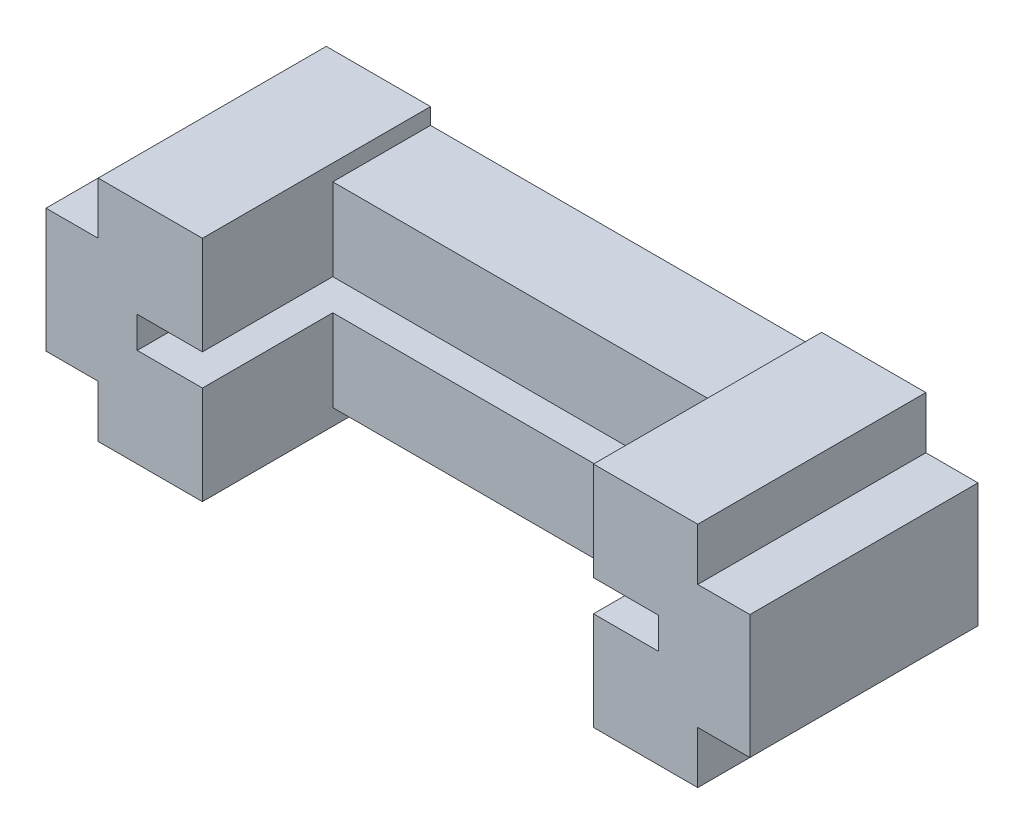
SolidWorks part; units mm, degrees
ref_plane "Front Plane" through (0, 0, 0) normal (0, 0, 1) x (1, 0, 0)
ref_plane "Top Plane" through (0, 0, 0) normal (0, 1, 0) x (1, 0, 0)
ref_plane "Right Plane" through (0, 0, 0) normal (1, 0, 0) x (0, 0, -1)
sketch "Sketch1" plane through (0, 0, 0) normal (0, 0, 1) x (1, 0, 0)
  line L1 (-29.21, -11.1125) -> (29.21, -11.1125)
  line L2 (-34.29, -6.0325) -> (-34.29, 6.0325)
  line L3 (-29.21, 11.1125) -> (29.21, 11.1125)
  line L4 (34.29, -6.0325) -> (34.29, 6.0325)
  line L9 (-34.29, 6.0325) -> (-29.21, 6.0325)
  line L10 (-29.21, 11.1125) -> (-29.21, 6.0325)
  line L13 (-34.29, -6.0325) -> (-29.21, -6.0325)
  line L14 (-29.21, -11.1125) -> (-29.21, -6.0325)
  line L17 (34.29, -6.0325) -> (29.21, -6.0325)
  line L18 (29.21, -11.1125) -> (29.21, -6.0325)
  line L21 (34.29, 6.0325) -> (29.21, 6.0325)
  line L22 (29.21, 11.1125) -> (29.21, 6.0325)
  point P0 (0, 0)
  point P1 (0, 0)
  point P2 (0, 11.1125)
  point P3 (0, 0)
  point P4 (-34.29, 0)
  point P18 (-53.7979, -27.4266)
  dimension "D1" = 68.58
  dimension "D2" = 22.225
  dimension "D3" = 5.08
extrude "Boss-Extrude1" add sketch "Sketch1" along normal blind 9.525
sketch "Sketch3" plane through (0, 0, 9.525) normal (0, 0, 1) x (1, 0, 0)
  line L0 (29.21, 11.1125) -> (-29.21, 11.1125) construction
  line L1 (-29.21, 11.1125) -> (-19.05, 11.1125)
  line L2 (-34.29, 6.0325) -> (-34.29, -6.0325)
  line L3 (-29.21, -11.1125) -> (-19.05, -11.1125)
  line L4 (-19.05, 11.1125) -> (-19.05, 1.524)
  line L5 (-29.21, -11.1125) -> (29.21, -11.1125) construction
  line L6 (0, 0) -> (0, 11.1125) construction
  line L7 (-19.05, 1.524) -> (-25.4, 1.524)
  line L9 (-19.05, -1.524) -> (-25.4, -1.524)
  line L10 (-25.4, 1.524) -> (-25.4, -1.524)
  line L11 (-19.05, -1.524) -> (-19.05, -11.1125)
  line L12 (19.05, -1.524) -> (19.05, -11.1125)
  line L13 (25.4, 1.524) -> (25.4, -1.524)
  line L14 (19.05, -1.524) -> (25.4, -1.524)
  line L15 (19.05, 1.524) -> (25.4, 1.524)
  line L16 (19.05, 11.1125) -> (19.05, 1.524)
  line L17 (29.21, -11.1125) -> (19.05, -11.1125)
  line L18 (34.29, 6.0325) -> (34.29, -6.0325)
  line L19 (29.21, 11.1125) -> (19.05, 11.1125)
  line L20 (-34.29, 6.0325) -> (-34.29, -6.0325) construction
  line L21 (29.21, -11.1125) -> (29.21, -6.0325) construction
  line L24 (-34.29, 6.0325) -> (-29.21, 6.0325)
  line L25 (-29.21, 11.1125) -> (-29.21, 6.0325)
  line L26 (-29.21, -6.0325) -> (-34.29, -6.0325)
  line L27 (-29.21, -6.0325) -> (-29.21, -11.1125)
  line L32 (34.29, -6.0325) -> (29.21, -6.0325)
  line L33 (29.21, -11.1125) -> (29.21, -6.0325)
  line L34 (29.21, -6.0325) -> (34.29, -6.0325) construction
  line L37 (34.29, 6.0325) -> (29.21, 6.0325)
  line L38 (29.21, 11.1125) -> (29.21, 6.0325)
  line L39 (34.29, -6.0325) -> (34.29, 6.0325) construction
  point P12 (-25.4, 0)
  point P43 (29.21, 8.3912)
  dimension "D1" = 6.35
  dimension "D2" = 3.048
  dimension "D4" = 19.05
extrude "Boss-Extrude2" add sketch "Sketch3" along normal blind 12.7
sketch "Sketch4" plane through (0, 0, 9.525) normal (0, 0, 1) x (1, 0, 0)
  line L1 (-25.4, -1.524) -> (25.4, -1.524)
  line L2 (-25.4, -1.524) -> (-25.4, 1.524)
  line L3 (-25.4, 1.524) -> (25.4, 1.524)
  line L4 (25.4, -1.524) -> (25.4, 1.524)
extrude "Cut-Extrude1" cut sketch "Sketch4" against normal blind 6.096
sketch "Sketch5" plane through (0, 0, 9.525) normal (0, 0, 1) x (1, 0, 0)
  line L0 (19.05, 11.1125) -> (-19.05, 11.1125) construction
  line L1 (-19.05, 11.1125) -> (19.05, 11.1125)
  line L2 (-19.05, 11.1125) -> (-19.05, 9.525)
  line L3 (-19.05, 9.525) -> (19.05, 9.525)
  line L4 (19.05, 11.1125) -> (19.05, 9.525)
  line L5 (0, 0) -> (12.7, 0) construction
  line L6 (19.05, -11.1125) -> (19.05, -9.525)
  line L7 (-19.05, -9.525) -> (19.05, -9.525)
  line L8 (-19.05, -11.1125) -> (-19.05, -9.525)
  line L9 (-19.05, -11.1125) -> (19.05, -11.1125)
  line L10 (-19.05, 1.524) -> (-19.05, 11.1125) construction
  point P6 (0, 9.525)
  point P14 (0, 0)
  dimension "D1" = 1.5875
extrude "Cut-Extrude2" cut sketch "Sketch5" against normal through all both and the other way through all
